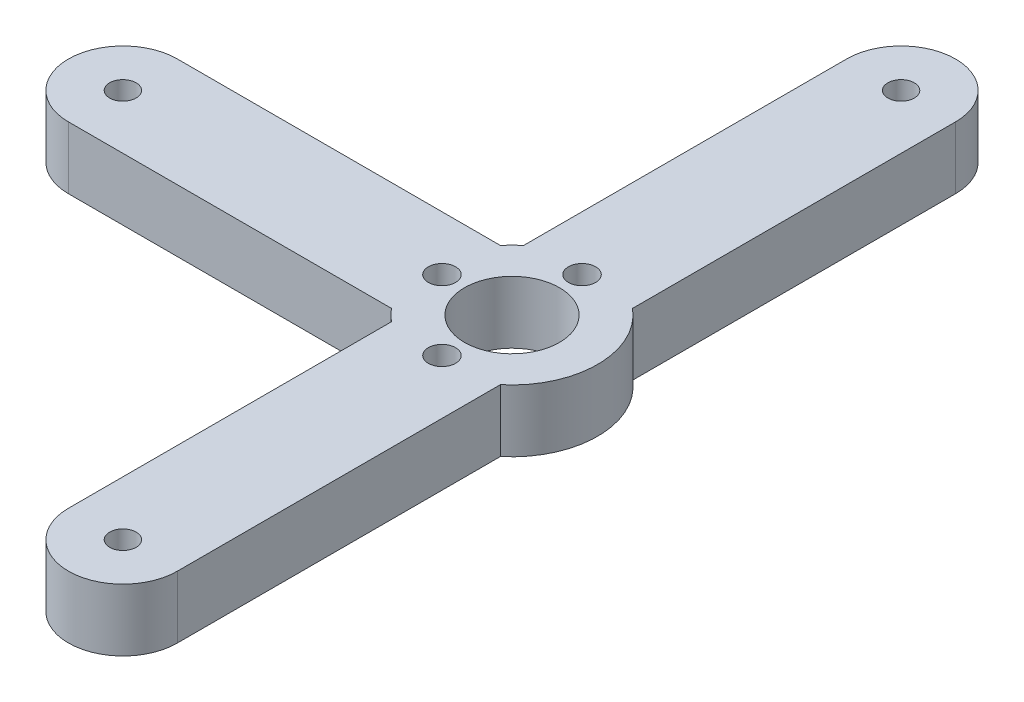
SolidWorks part; units mm, degrees
other "Rear Support Plate Left"
ref_plane "Front Plane" through (0, 0, 0) normal (0, 0, 1) x (1, 0, 0)
ref_plane "Top Plane" through (0, 0, 0) normal (0, 1, 0) x (1, 0, 0)
ref_plane "Right Plane" through (0, 0, 0) normal (1, 0, 0) x (0, 0, -1)
sketch3d "Base Outline Sketch datum points"
  point P0 (0, 149, 0)
  point P1 (10, 149, 0)
  point P2 (0, 149, -10)
ref_plane "Base Outline Sketch plane" through (0, 149, 0) normal (0, 1, 0) x (1, 0, 0)
sketch "Base Outline Sketch" plane through (0, 149, 0) normal (0, 1, 0) x (1, 0, 0)
  line L0 (-64.7769, -7) -> (-106.2917, -7)
  line L1 (-106.2917, 7) -> (-64.7769, 7)
  line L2 (-63.2917, -50) -> (-63.2917, -8.4853)
  line L3 (-63.2917, 8.4853) -> (-63.2917, 50)
  line L4 (-49.2917, -8.4853) -> (-49.2917, -50)
  line L5 (-49.2917, 50) -> (-49.2917, 8.4853)
  arc A0 (-63.2917, -8.4853) -> (-64.7769, -7) centre (-56.2917, 0) cw
  arc A1 (-106.2917, -7) -> (-106.2917, 7) centre (-106.2917, 0) cw
  arc A2 (-64.7769, 7) -> (-63.2917, 8.4853) centre (-56.2917, 0) cw
  arc A3 (-49.2917, -50) -> (-63.2917, -50) centre (-56.2917, -50) cw
  arc A4 (-63.2917, 50) -> (-49.2917, 50) centre (-56.2917, 50) cw
  arc A5 (-49.2917, 8.4853) -> (-49.2917, -8.4853) centre (-56.2917, 0) cw
  circle A6 centre (-56.2917, 0) radius 6.1
  circle A7 centre (-106.2917, 0) radius 3.1
  circle A8 centre (-56.2917, 50) radius 3.1
  circle A9 centre (-56.2917, -50) radius 3.1
extrude "Base Outline" add sketch "Base Outline Sketch" along normal blind 1 separate body
sketch3d "Interface Profile 2 Sketch datum points"
  point P0 (0, 150, 0)
  point P1 (10, 150, 0)
  point P2 (0, 150, -10)
ref_plane "Interface Profile 2 Sketch plane" through (0, 150, 0) normal (0, 1, 0) x (1, 0, 0)
sketch "Interface Profile 2 Sketch" plane through (0, 150, 0) normal (0, 1, 0) x (1, 0, 0)
  line L0 (-64.7769, -7) -> (-106.2917, -7)
  line L1 (-106.2917, 7) -> (-64.7769, 7)
  line L2 (-63.2917, -50) -> (-63.2917, -8.4853)
  line L3 (-63.2917, 8.4853) -> (-63.2917, 50)
  line L4 (-49.2917, -8.4853) -> (-49.2917, -50)
  line L5 (-49.2917, 50) -> (-49.2917, 8.4853)
  arc A0 (-63.2917, -8.4853) -> (-64.7769, -7) centre (-56.2917, 0) cw
  arc A1 (-106.2917, -7) -> (-106.2917, 7) centre (-106.2917, 0) cw
  arc A2 (-64.7769, 7) -> (-63.2917, 8.4853) centre (-56.2917, 0) cw
  arc A3 (-49.2917, -50) -> (-63.2917, -50) centre (-56.2917, -50) cw
  arc A4 (-63.2917, 50) -> (-49.2917, 50) centre (-56.2917, 50) cw
  arc A5 (-49.2917, 8.4853) -> (-49.2917, -8.4853) centre (-56.2917, 0) cw
  circle A6 centre (-56.2917, 0) radius 6.1
  circle A7 centre (-106.2917, 0) radius 3.1
  circle A8 centre (-56.2917, 50) radius 3.1
  circle A9 centre (-56.2917, -50) radius 3.1
  circle A10 centre (-56.2917, 9) radius 1.1
  circle A11 centre (-65.2917, 0) radius 1.1
  circle A12 centre (-56.2917, -9) radius 1.1
extrude "Interface Profile 2" add sketch "Interface Profile 2 Sketch" along normal blind 0.6
sketch3d "Interface Profile 3 Sketch datum points"
  point P0 (0, 150.6, 0)
  point P1 (10, 150.6, 0)
  point P2 (0, 150.6, -10)
ref_plane "Interface Profile 3 Sketch plane" through (0, 150.6, 0) normal (0, 1, 0) x (1, 0, 0)
sketch "Interface Profile 3 Sketch" plane through (0, 150.6, 0) normal (0, 1, 0) x (1, 0, 0)
  line L0 (-64.7769, -7) -> (-106.2917, -7)
  line L1 (-106.2917, 7) -> (-64.7769, 7)
  line L2 (-63.2917, -50) -> (-63.2917, -8.4853)
  line L3 (-63.2917, 8.4853) -> (-63.2917, 50)
  line L4 (-49.2917, -8.4853) -> (-49.2917, -50)
  line L5 (-49.2917, 50) -> (-49.2917, 8.4853)
  arc A0 (-63.2917, -8.4853) -> (-64.7769, -7) centre (-56.2917, 0) cw
  arc A1 (-106.2917, -7) -> (-106.2917, 7) centre (-106.2917, 0) cw
  arc A2 (-64.7769, 7) -> (-63.2917, 8.4853) centre (-56.2917, 0) cw
  arc A3 (-49.2917, -50) -> (-63.2917, -50) centre (-56.2917, -50) cw
  arc A4 (-63.2917, 50) -> (-49.2917, 50) centre (-56.2917, 50) cw
  arc A5 (-49.2917, 8.4853) -> (-49.2917, -8.4853) centre (-56.2917, 0) cw
  circle A6 centre (-106.2917, 0) radius 1.7
  circle A7 centre (-56.2917, 50) radius 1.7
  circle A8 centre (-56.2917, 0) radius 6.1
  circle A9 centre (-56.2917, -50) radius 1.7
  circle A10 centre (-56.2917, 9) radius 1.1
  circle A11 centre (-65.2917, 0) radius 1.1
  circle A12 centre (-56.2917, -9) radius 1.1
extrude "Interface Profile 3" add sketch "Interface Profile 3 Sketch" along normal blind 2.4
sketch3d "Interface Profile 4 Sketch datum points"
  point P0 (0, 153, 0)
  point P1 (10, 153, 0)
  point P2 (0, 153, -10)
ref_plane "Interface Profile 4 Sketch plane" through (0, 153, 0) normal (0, 1, 0) x (1, 0, 0)
sketch "Interface Profile 4 Sketch" plane through (0, 153, 0) normal (0, 1, 0) x (1, 0, 0)
  line L0 (-64.7769, -7) -> (-106.2917, -7)
  line L1 (-106.2917, 7) -> (-64.7769, 7)
  line L2 (-63.2917, -50) -> (-63.2917, -8.4853)
  line L3 (-63.2917, 8.4853) -> (-63.2917, 50)
  line L4 (-49.2917, -8.4853) -> (-49.2917, -50)
  line L5 (-49.2917, 50) -> (-49.2917, 8.4853)
  arc A0 (-63.2917, -8.4853) -> (-64.7769, -7) centre (-56.2917, 0) cw
  arc A1 (-106.2917, -7) -> (-106.2917, 7) centre (-106.2917, 0) cw
  arc A2 (-64.7769, 7) -> (-63.2917, 8.4853) centre (-56.2917, 0) cw
  arc A3 (-49.2917, -50) -> (-63.2917, -50) centre (-56.2917, -50) cw
  arc A4 (-63.2917, 50) -> (-49.2917, 50) centre (-56.2917, 50) cw
  arc A5 (-49.2917, 8.4853) -> (-49.2917, -8.4853) centre (-56.2917, 0) cw
  circle A6 centre (-106.2917, 0) radius 1.7
  circle A7 centre (-56.2917, 50) radius 1.7
  circle A8 centre (-56.2917, 9) radius 1.75
  circle A9 centre (-65.2917, 0) radius 1.75
  circle A10 centre (-56.2917, 0) radius 6.1
  circle A11 centre (-56.2917, -9) radius 1.75
  circle A12 centre (-56.2917, -50) radius 1.7
extrude "Interface Profile 4" add sketch "Interface Profile 4 Sketch" along normal blind 4
